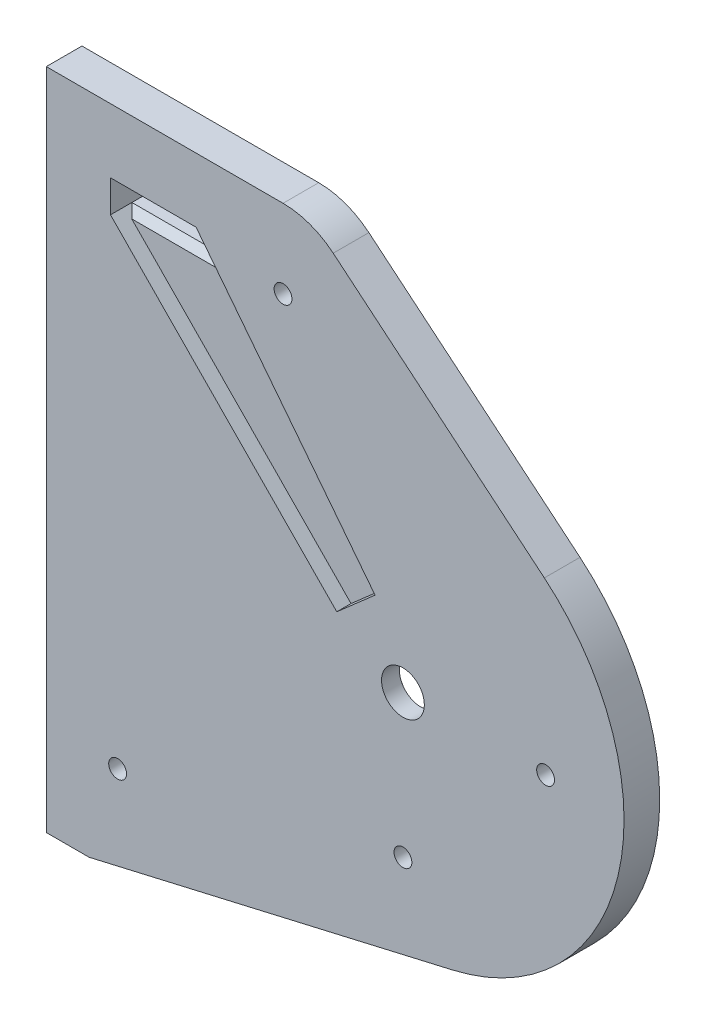
SolidWorks part; units mm, degrees
ref_plane "Front Plane" through (0, 0, 0) normal (0, 0, 1) x (1, 0, 0)
ref_plane "Top Plane" through (0, 0, 0) normal (0, 1, 0) x (1, 0, 0)
ref_plane "Right Plane" through (0, 0, 0) normal (1, 0, 0) x (0, 0, -1)
sketch "Sketch1" plane through (0, 0, 0) normal (0, 0, 1) x (1, 0, 0)
  line L0 (0, 21) -> (0, 15) construction
  line L1 (0, -66) -> (0, 15) construction
  line L2 (0, -66) -> (0, -72) construction
  line L3 (0, -72) -> (6, -72) construction
  line L4 (6, -72) -> (56.9883, -60.202) construction
  line L5 (50, -50) -> (10, -59.2554) construction
  line L6 (69.8263, -6.169) -> (40.2272, 18.4562) construction
  line L7 (0, 21) -> (33.1921, 21) construction
  line L8 (0, 21) -> (0, 15)
  line L9 (0, -54) -> (-64, -54)
  line L10 (-65, -55) -> (-65, -61)
  line L11 (-60, -66) -> (5.4214, -66)
  line L12 (6.5633, -65.8679) -> (55.7094, -54.3393)
  line L13 (65.989, -10.7815) -> (36.3898, 13.8437)
  line L14 (33.1921, 15) -> (-60, 15)
  line L15 (-65, 10) -> (-65, 6)
  line L16 (-64, 5) -> (0, 5)
  line L17 (0, 5) -> (0, -54)
  line L26 (0, 5) -> (0, -54)
  line L27 (0, -66) -> (0, 15)
  line L28 (0, -66) -> (0, -72)
  line L29 (0, -72) -> (6, -72)
  line L30 (6, -72) -> (56.9883, -60.202)
  line L31 (69.8263, -6.169) -> (40.2272, 18.4562)
  line L32 (0, 21) -> (33.1921, 21)
  line L86 (9, 12) -> (21, 12)
  line L87 (21, 12) -> (21, 7.5)
  line L88 (21, 7.5) -> (9, 7.5)
  line L89 (9, 7.5) -> (9, 12)
  line L90 (15, 11) -> (15, 12) construction
  line L91 (10, 11) -> (20, 11) construction
  line L92 (10, 9.75) -> (9, 9.75) construction
  line L93 (10, 8.5) -> (10, 11) construction
  circle A0 centre (50, -30) radius 3
  circle A2 centre (50, -30) radius 20 construction
  circle A3 centre (50, -50) radius 1.25
  circle A4 centre (70, -30) radius 1.25
  arc A6 (30.1546, -32.4819) -> (69.844, -32.493) centre (50, -30) ccw construction
  circle A7 centre (33.1921, 10) radius 1.25
  arc A9 (-64, -54) -> (-65, -55) centre (-64, -55) ccw
  arc A10 (-65, -61) -> (-60, -66) centre (-60, -61) ccw
  arc A11 (5.4214, -66) -> (6.5633, -65.8679) centre (5.4214, -61) ccw
  arc A12 (55.7094, -54.3393) -> (65.989, -10.7815) centre (50, -30) ccw
  arc A13 (36.3898, 13.8437) -> (33.1921, 15) centre (33.1921, 10) ccw
  arc A14 (-60, 15) -> (-65, 10) centre (-60, 10) ccw
  arc A15 (-65, 6) -> (-64, 5) centre (-64, 6) ccw
  arc A24 (56.9883, -60.202) -> (69.8263, -6.169) centre (50, -30) ccw construction
  arc A25 (40.2272, 18.4562) -> (33.1921, 21) centre (33.1921, 10) ccw construction
  arc A26 (56.9883, -60.202) -> (69.8263, -6.169) centre (50, -30) ccw
  arc A27 (40.2272, 18.4562) -> (33.1921, 21) centre (33.1921, 10) ccw
  circle A28 centre (10, -59.2554) radius 1.25
  dimension "D1" = 6
  dimension "D3" = 2.5
  dimension "D4" = 10
  dimension "D5" = 4.5
  dimension "D6" = 12
  dimension "D2" = 0
extrude "Boss-Extrude1" add sketch "Sketch1" along normal blind 5
sketch "Sketch2" plane through (0, 0, 5) normal (0, 0, 1) x (1, 0, 0)
  line L4 (9, 7.5) -> (40.7251, -24.8312)
  line L5 (40.7251, -24.8312) -> (46.0944, -20.1264)
  line L6 (46.0944, -20.1264) -> (21, 12)
  line L7 (43.4097, -22.4788) -> (50, -30) construction
  line L8 (9, 7.5) -> (21, 12)
  circle A2 centre (20, 8) radius 3 construction
  circle A4 centre (20, 8) radius 3 construction
  circle A5 centre (50, -30) radius 3 construction
  circle A6 centre (50, -30) radius 3 construction
  point P12 (9, 7.5)
  point P15 (21, 12)
  dimension "D3" = 3
  dimension "D4" = 10
  dimension "D1" = 30
  dimension "D2" = 38
extrude "Cut-Extrude1" cut sketch "Sketch2" against normal blind 2
sketch "Sketch3" plane through (0, 0, 0) normal (0, 0, -1) x (-1, 0, 0)
  line L1 (-42.6099, -30) -> (-46.305, -23.6)
  line L2 (-46.305, -23.6) -> (-53.695, -23.6)
  line L3 (-53.695, -23.6) -> (-57.3901, -30)
  line L4 (-57.3901, -30) -> (-53.695, -36.4)
  line L5 (-53.695, -36.4) -> (-46.305, -36.4)
  line L6 (-46.305, -36.4) -> (-42.6099, -30)
  circle A0 centre (-50, -30) radius 6.4 construction
  dimension "D1" = 12.8
extrude "Cut-Extrude2" cut sketch "Sketch3" against normal blind 2.5
chamfer "Chamfer1" distance 1 angle 45 2 edges at (15, 7.5, 3) (21, 9.75, 3)
